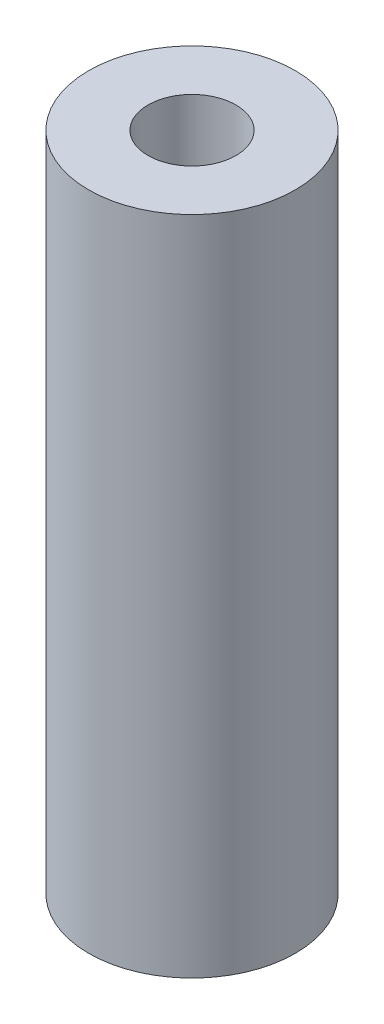
SolidWorks part; units mm, degrees
ref_plane "Front Plane" through (0, 0, 0) normal (0, 0, 1) x (1, 0, 0)
ref_plane "Top Plane" through (0, 0, 0) normal (0, 1, 0) x (1, 0, 0)
ref_plane "Right Plane" through (0, 0, 0) normal (1, 0, 0) x (0, 0, -1)
sketch "Sketch1" plane through (0, 0, 0) normal (0, 1, 0) x (1, 0, 0)
  circle A0 centre (0, 0) radius 3.3734
  circle A1 centre (0, 0) radius 7.9375
  dimension "D1" = 6.7469
  dimension "D2" = 15.875
extrude "Boss-Extrude1" add sketch "Sketch1" along normal blind 50.8
